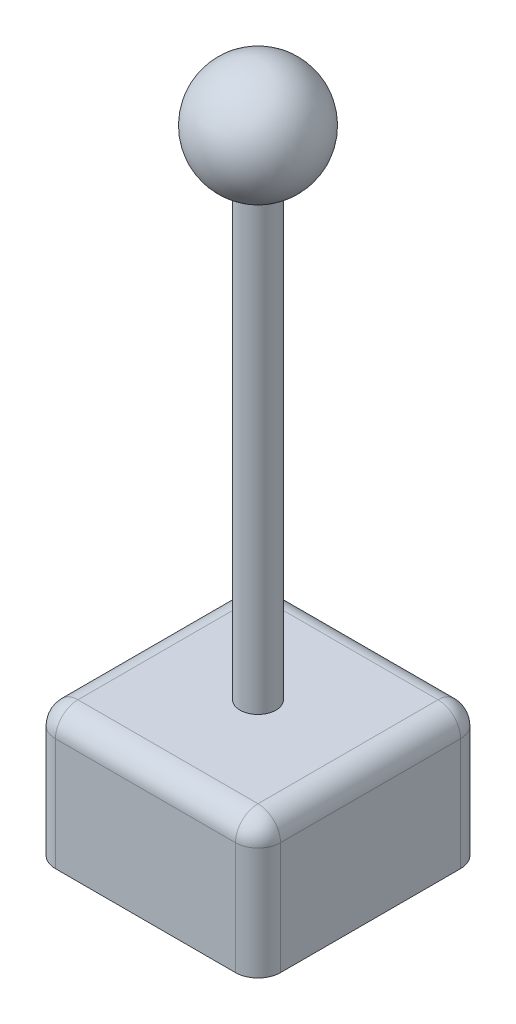
SolidWorks part; units mm, degrees
ref_plane "前视基准面" through (0, 0, 0) normal (0, 0, 1) x (1, 0, 0)
ref_plane "上视基准面" through (0, 0, 0) normal (0, 1, 0) x (1, 0, 0)
ref_plane "右视基准面" through (0, 0, 0) normal (1, 0, 0) x (0, 0, -1)
sketch "草图1" plane through (0, 0, 0) normal (0, 1, 0) x (1, 0, 0)
  line L1 (-25, 25) -> (25, 25)
  line L2 (-25, 25) -> (-25, -25)
  line L3 (-25, -25) -> (25, -25)
  line L4 (25, 25) -> (25, -25)
  point P7 (18.4579, -1.8692)
  dimension "D1" = 50
  dimension "D2" = 50
  dimension "D3" = 25
  dimension "D4" = 25
extrude "凸台-拉伸1" add sketch "草图1" along normal blind 30
fillet "圆角1" radius 5 8 edges at (25, 15, -25) (0, 30, -25) (-25, 15, -25) (25, 30, 0) (25, 15, 25) (-25, 15, 25) (-25, 30, 0) (0, 30, 25)
sketch "草图2" plane through (0, 30, 0) normal (0, 1, 0) x (1, 0, 0)
  circle A0 centre (0, 0) radius 4
extrude "凸台-拉伸2" add sketch "草图2" along normal blind 100
sketch "草图3" plane through (0, 0, 0) normal (0, 0, 1) x (1, 0, 0)
  line L0 (0, 130) -> (0, 128)
  line L1 (4, 130) -> (-4, 130) construction
  line L2 (0, 130) -> (0, 153)
  arc A0 (0, 153) -> (0, 128) centre (0, 140.5) cw
revolve "旋转1" add sketch "草图3" angle 360 about L2
